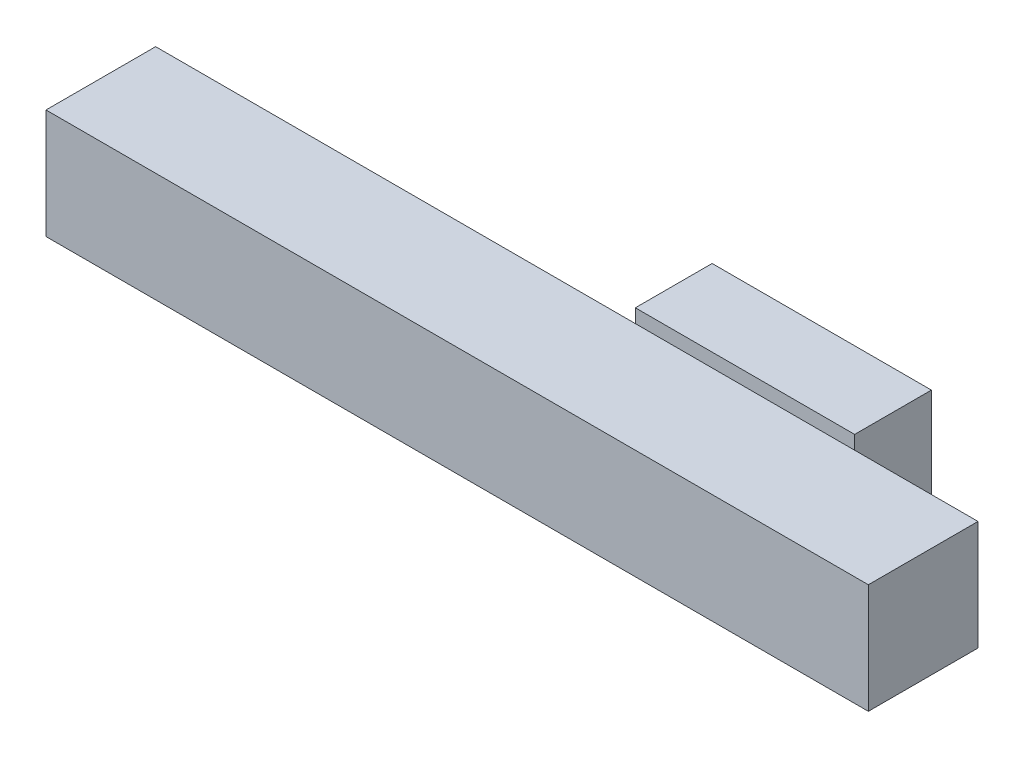
SolidWorks part; units mm, degrees
ref_plane "Front Plane" through (0, 0, 0) normal (0, 0, 1) x (1, 0, 0)
ref_plane "Top Plane" through (0, 0, 0) normal (0, 1, 0) x (1, 0, 0)
ref_plane "Right Plane" through (0, 0, 0) normal (1, 0, 0) x (0, 0, -1)
sketch "Sketch1" plane through (0, 0, 0) normal (0, 0, 1) x (1, 0, 0)
  line L1 (-40, -24.5) -> (40, -24.5)
  line L2 (-40, -24.5) -> (-40, 24.5)
  line L3 (-40, 24.5) -> (40, 24.5)
  line L4 (40, -24.5) -> (40, 24.5)
  line L5 (-40, -24.5) -> (40, 24.5) construction
  line L6 (-40, 24.5) -> (40, -24.5) construction
  point P0 (0, 0)
  dimension "D1" = 80
  dimension "D2" = 49
extrude "Boss-Extrude1" add sketch "Sketch1" along normal blind 28
sketch "Sketch2" plane through (0, 0, 28) normal (0, 0, 1) x (1, 0, 0)
  line L1 (-215, -20.5) -> (85, -20.5)
  line L2 (-215, -20.5) -> (-215, 19.5)
  line L3 (-215, 19.5) -> (85, 19.5)
  line L4 (85, -20.5) -> (85, 19.5)
  line L5 (40, -24.5) -> (40, 24.5) construction
  line L6 (40, 24.5) -> (-40, 24.5) construction
  point P0 (0, 0)
  dimension "D1" = 40
  dimension "D2" = 300
  dimension "D3" = 45
  dimension "D4" = 5
extrude "Boss-Extrude2" add sketch "Sketch2" along normal blind 40
